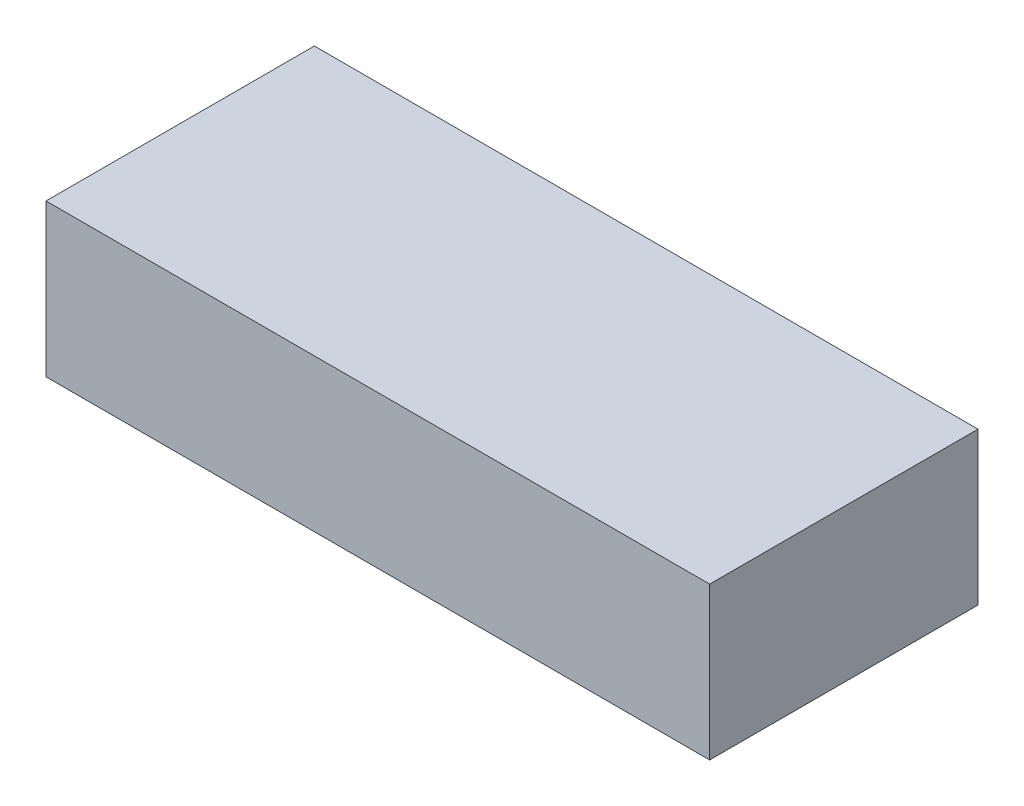
SolidWorks part; units mm, degrees
ref_plane "Front Plane" through (0, 0, 0) normal (0, 0, 1) x (1, 0, 0)
ref_plane "Top Plane" through (0, 0, 0) normal (0, 1, 0) x (1, 0, 0)
ref_plane "Right Plane" through (0, 0, 0) normal (1, 0, 0) x (0, 0, -1)
sketch "Sketch1" plane through (0, 0, 0) normal (0, 1, 0) x (1, 0, 0)
  line L1 (457.5, 0) -> (-457.5, 0)
  line L2 (457.5, 0) -> (457.5, 370)
  line L3 (457.5, 370) -> (-457.5, 370)
  line L4 (-457.5, 0) -> (-457.5, 370)
  point P4 (0, 0)
  point P6 (0, 370)
  dimension "D1" = 915
  dimension "D2" = 370
extrude "Boss-Extrude1" add sketch "Sketch1" against normal blind 210
